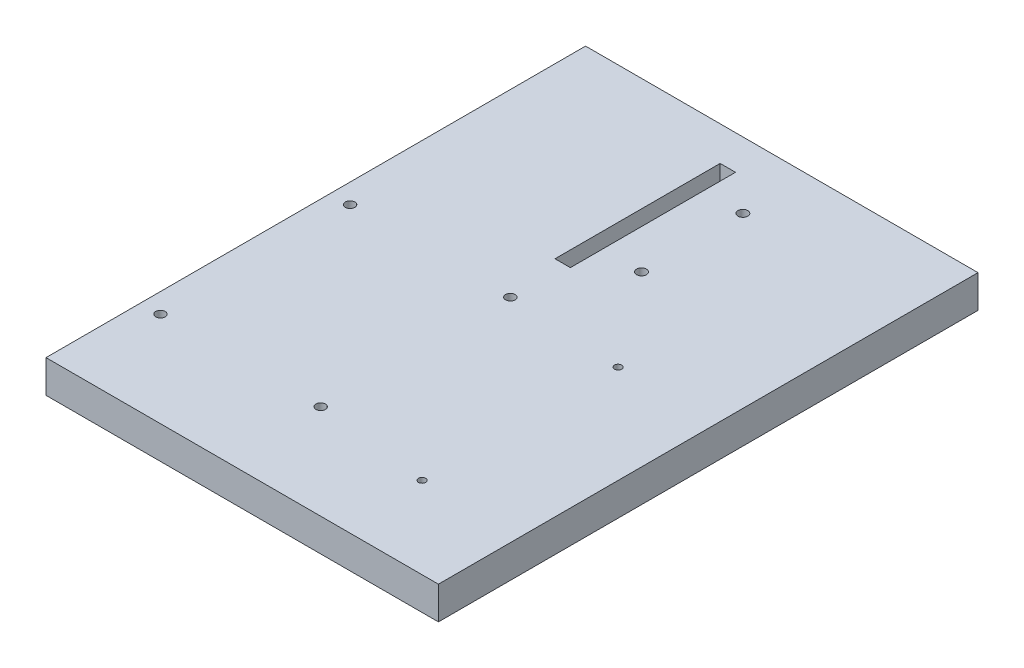
SolidWorks part; units mm, degrees
ref_plane "Front Plane" through (0, 0, 0) normal (0, 0, 1) x (1, 0, 0)
ref_plane "Top Plane" through (0, 0, 0) normal (0, 1, 0) x (1, 0, 0)
ref_plane "Right Plane" through (0, 0, 0) normal (1, 0, 0) x (0, 0, -1)
sketch "Sketch1" plane through (0, 0, 0) normal (0, 1, 0) x (1, 0, 0)
  line L1 (0, 0) -> (120, 0)
  line L2 (0, 0) -> (0, 165)
  line L3 (0, 165) -> (120, 165)
  line L4 (120, 0) -> (120, 165)
  dimension "D1" = 120
  dimension "D2" = 165
extrude "Base" add sketch "Sketch1" along normal blind 10
hole_wizard "Pi-MountHoles" positions "Sketch13" profile "Sketch14" counterbore size "M2.5" standard "ANSI Metric" end condition up to next
sketch "Sketch13" plane through (0, 0, 0) normal (0, -1, 0) x (-1, 0, 0)
  line L1 (0, 0) -> (-120, 0) construction
  line L2 (0, 165) -> (0, 0) construction
  point P0 (-6, 29)
  point P2 (-55, 29)
  point P4 (-55, 87)
  point P6 (-6, 87)
  dimension "D1" = 49
  dimension "D2" = 58
  dimension "D3" = 87
  dimension "D4" = 6
sketch "Sketch14" plane through (6, 0, -29) normal (1, 0, 0) x (0, 0, -1)
  line L0 (0, 0) -> (0, 10)
  line L1 (0, 10) -> (1.45, 10)
  line L3 (1.45, 10) -> (1.45, 2.1)
  line L4 (3, 2.1) -> (1.45, 2.1)
  line L5 (3, 2.1) -> (3, 0.025)
  line L6 (3, 0.025) -> (3.025, 0)
  line L7 (3.025, 0) -> (0, 0)
  line L8 (-3, 0.025) -> (-3.025, 0) construction
  line L11 (0, -6.35) -> (0, 107.95) construction
  dimension "Thru Hole Dia." = 2.9
  dimension "Thru Hole Depth" = 10
  dimension "C'Bore Dia." = 6
  dimension "C'Bore Depth" = 2.1
  dimension "Near C'Sink Dia." = 6.05
  dimension "Near C'Sink Angle" = 90
hole_wizard "Battery-MountHoles" positions "Sketch15" profile "Sketch16" counterbore size "M2" standard "ANSI Metric" end condition up to next
sketch "Sketch15" plane through (0, 0, 0) normal (0, -1, 0) x (-1, 0, 0)
  line L0 (0, 0) -> (-120, 0) construction
  circle A0 centre (-55, 87) radius 1.45 construction
  point P0 (-90, 25)
  point P2 (-90, 84.95)
  dimension "D1" = 59.95
  dimension "D2" = 25
  dimension "D3" = 35
sketch "Sketch16" plane through (90, 0, -25) normal (1, 0, 0) x (0, 0, -1)
  line L0 (0, 0) -> (0, 10)
  line L1 (0, 10) -> (1.1, 10)
  line L3 (1.1, 10) -> (1.1, 1.6)
  line L4 (2.5, 1.6) -> (1.1, 1.6)
  line L5 (2.5, 1.6) -> (2.5, 0.025)
  line L6 (2.5, 0.025) -> (2.525, 0)
  line L7 (2.525, 0) -> (0, 0)
  line L8 (-2.5, 0.025) -> (-2.525, 0) construction
  line L11 (0, -6.35) -> (0, 107.95) construction
  dimension "Thru Hole Dia." = 2.2
  dimension "Thru Hole Depth" = 10
  dimension "C'Bore Dia." = 5
  dimension "C'Bore Depth" = 1.6
  dimension "Near C'Sink Dia." = 5.05
  dimension "Near C'Sink Angle" = 90
sketch "Sketch17" plane through (0, 10, 0) normal (0, 1, 0) x (1, 0, 0)
  line L1 (51.65, 154.5) -> (56.35, 154.5)
  line L2 (51.65, 154.5) -> (51.65, 104)
  line L3 (51.65, 104) -> (56.35, 104)
  line L4 (56.35, 154.5) -> (56.35, 104)
  circle A4 centre (55, 87) radius 1.45 construction
  dimension "D1" = 3.35
  dimension "D4" = 17
  dimension "D2" = 4.7
  dimension "D3" = 50.5
extrude "StepperBracketSlot" cut sketch "Sketch17" against normal up to surface (10 mm away) up to face at (90, 0, -27.525)
sketch "Sketch18" plane through (0, 10, 0) normal (0, 1, 0) x (1, 0, 0)
  line L1 (56.35, 104) -> (56.35, 154.5) construction
  circle A0 centre (68.35, 144.75) radius 1.5
  circle A1 centre (68.35, 113.75) radius 1.5
  point P10 (56.35, 129.25)
  dimension "D1" = 3
  dimension "D2" = 31
  dimension "D3" = 15.5
  dimension "D4" = 12
extrude "AngleBracket-MountHoles" cut sketch "Sketch18" against normal up to surface (10 mm away) up to face at (54, 0, -129.25)
equation "\"D3@Sketch18\"=\"D2@Sketch18\"/2"
